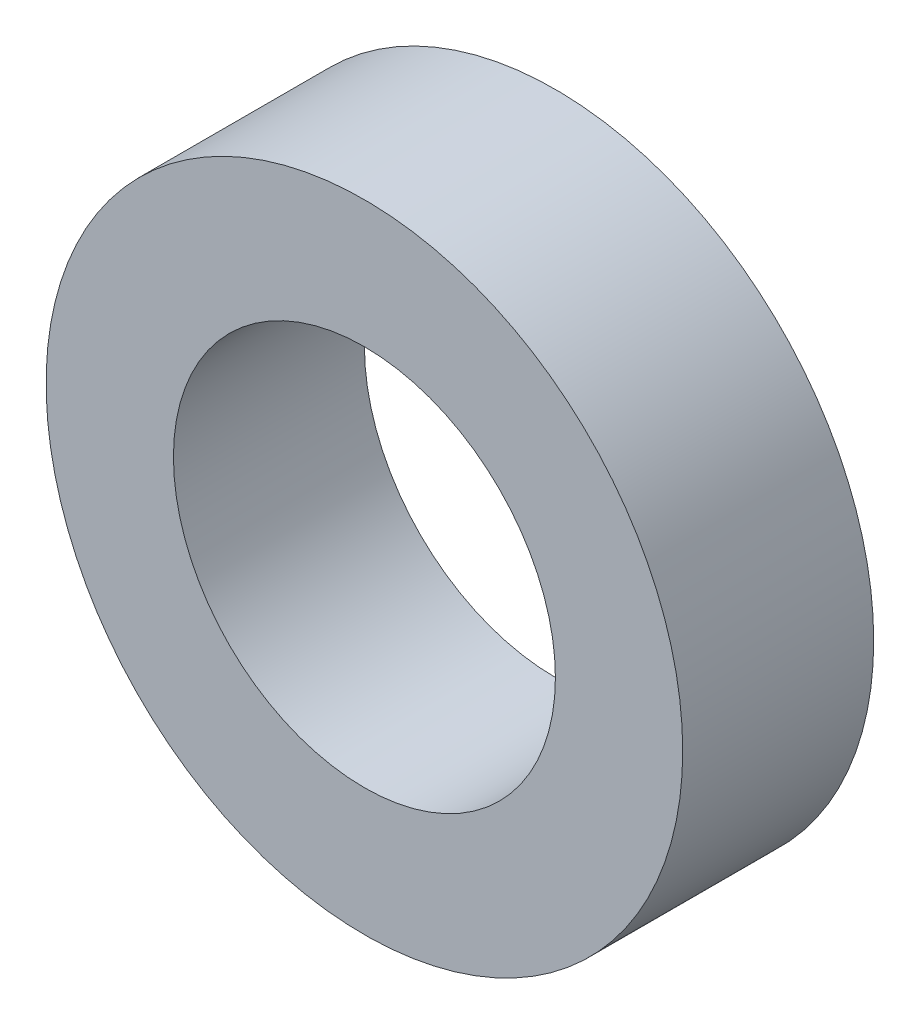
SolidWorks part; units mm, degrees
ref_plane "정면" through (0, 0, 0) normal (0, 0, 1) x (1, 0, 0)
ref_plane "윗면" through (0, 0, 0) normal (0, 1, 0) x (1, 0, 0)
ref_plane "우측면" through (0, 0, 0) normal (1, 0, 0) x (0, 0, -1)
sketch "스케치1" plane through (0, 0, 0) normal (0, 0, 1) x (1, 0, 0)
  circle A0 centre (0, 0) radius 15
  circle A1 centre (0, 0) radius 25
  dimension "D1" = 10
  dimension "D2" = 30
extrude "보스-돌출1" add sketch "스케치1" along normal blind 15
